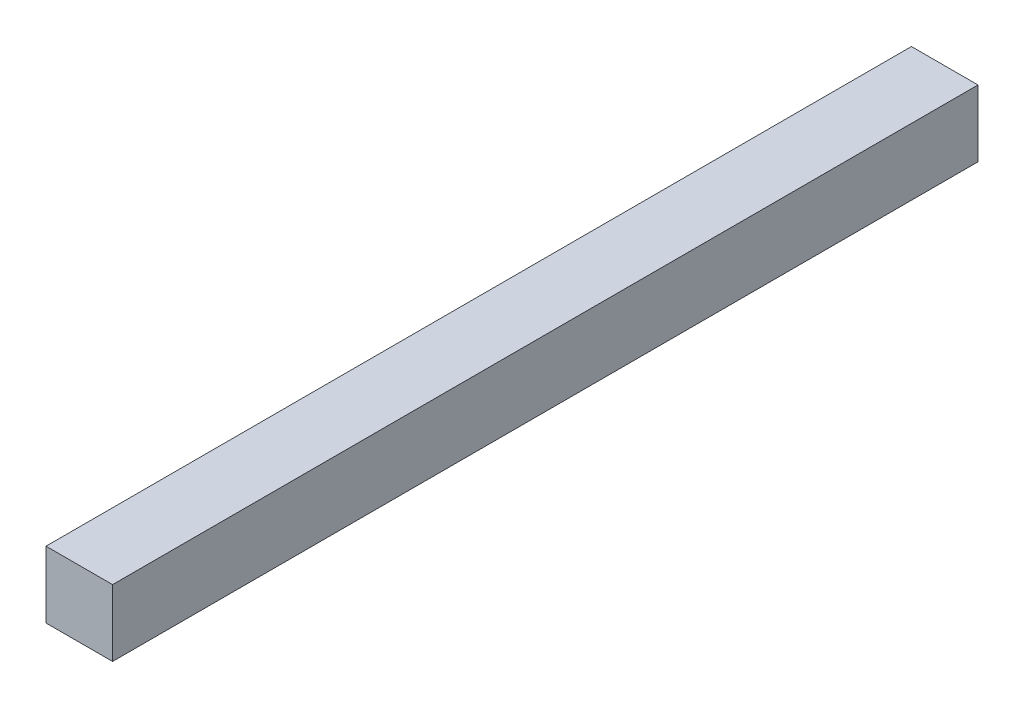
SolidWorks part; units mm, degrees
ref_plane "Front" through (0, 0, 0) normal (0, 0, 1) x (1, 0, 0)
ref_plane "Top" through (0, 0, 0) normal (0, 1, 0) x (1, 0, 0)
ref_plane "Right" through (0, 0, 0) normal (1, 0, 0) x (0, 0, -1)
sketch "Sketch1" plane through (0, 0, 0) normal (0, 0, 1) x (1, 0, 0)
  line L1 (0, 0) -> (-2.54, 0)
  line L2 (0, 0) -> (0, 2.54)
  line L3 (0, 2.54) -> (-2.54, 2.54)
  line L4 (-2.54, 0) -> (-2.54, 2.54)
  dimension "D1" = 2.54
  dimension "D2" = 2.54
extrude "Boss-Extrude1" add sketch "Sketch1" along normal blind 33.02
